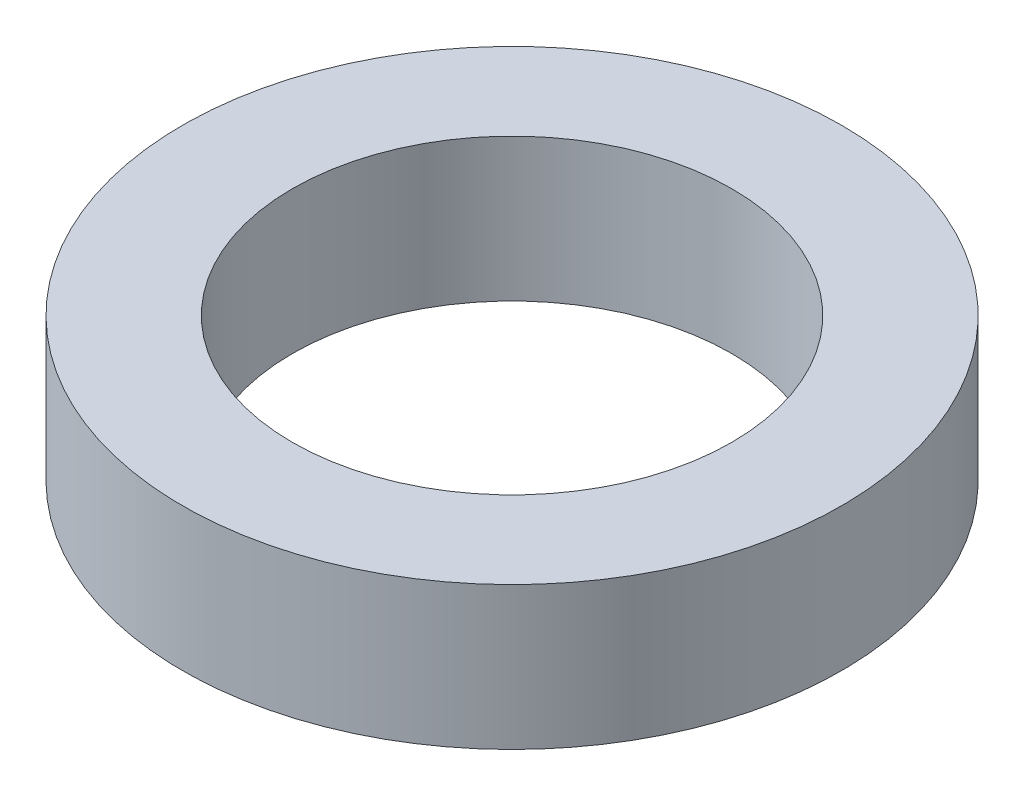
SolidWorks part; units mm, degrees
material "Plain Carbon Steel"
ref_plane "Front Plane" through (0, 0, 0) normal (0, 0, 1) x (1, 0, 0)
ref_plane "Top Plane" through (0, 0, 0) normal (0, 1, 0) x (1, 0, 0)
ref_plane "Right Plane" through (0, 0, 0) normal (1, 0, 0) x (0, 0, -1)
sketch "Sketch1" plane through (0, 0, 0) normal (0, 1, 0) x (1, 0, 0)
  circle A0 centre (0, 0) radius 20
  circle A1 centre (0, 0) radius 30
  dimension "D1" = 40
  dimension "D2" = 60
extrude "Boss-Extrude1" add sketch "Sketch1" along normal blind 13
